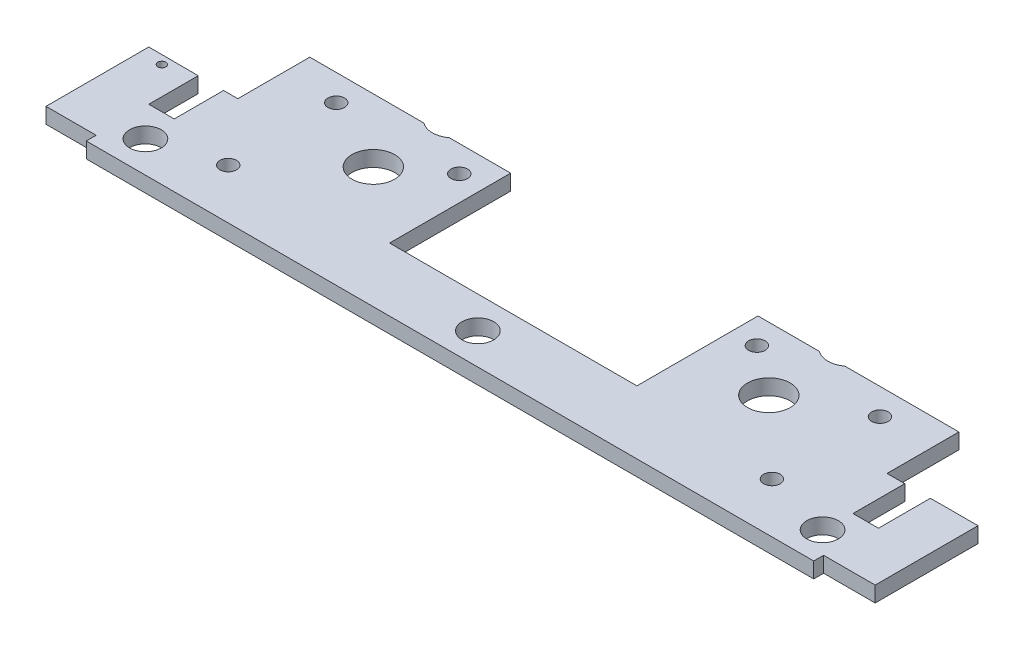
SolidWorks part; units mm, degrees
material "Copper"
ref_plane "Front Plane" through (0, 0, 0) normal (0, 0, 1) x (1, 0, 0)
ref_plane "Top Plane" through (0, 0, 0) normal (0, 1, 0) x (1, 0, 0)
ref_plane "Right Plane" through (0, 0, 0) normal (1, 0, 0) x (0, 0, -1)
sketch "Sketch1" plane through (0, 0, 0) normal (0, 1, 0) x (1, 0, 0)
  line L0 (44.3513, -40.0144) -> (37.1363, -40.0144)
  line L1 (0, 0) -> (0, -46.6159) construction
  line L2 (-19.6486, -28.7674) -> (44.3513, -28.7674) construction
  line L3 (-36.4337, -40.0144) -> (-36.4337, -46.6159)
  line L4 (37.1363, -40.0144) -> (37.1363, -46.6159)
  line L5 (-36.4337, -40.0144) -> (-43.6487, -40.0144)
  line L6 (-32.4727, -10.3704) -> (-32.4727, -29.6479)
  line L7 (-32.4727, 38.1938) -> (-32.4727, -29.6479) construction
  line L8 (-19.6486, -20.6394) -> (46.7444, -20.6394) construction
  line L9 (-42.3787, -29.6159) -> (-32.4727, -29.6479)
  line L10 (-12.1556, -10.3704) -> (-32.4727, -10.3704)
  line L11 (29.9683, -46.6159) -> (37.1363, -46.6159)
  line L12 (44.3513, -40.0144) -> (44.3513, -31.6519)
  line L13 (42.3513, -29.6159) -> (38.7463, -29.6159)
  line L14 (38.7463, -29.6159) -> (33.1753, -29.6479)
  line L15 (-11.5577, -34.6159) -> (-12.1556, -34.6159)
  line L16 (-12.1556, -34.6159) -> (-12.1556, -10.3704)
  line L17 (33.1753, -29.6479) -> (33.1753, 37.3661) construction
  line L18 (33.1753, -12.9294) -> (33.1753, -29.6479)
  line L19 (12.8581, -10.3704) -> (33.1753, -10.3704)
  line L20 (33.1753, -10.3704) -> (33.1753, -12.9294)
  line L21 (-43.6487, -29.6479) -> (-43.6487, -44.6339) construction
  line L22 (-43.6487, -30.8859) -> (-43.6487, -40.0144)
  line L23 (-36.4337, -46.6159) -> (-30.0837, -46.6159)
  line L24 (-30.0837, -46.6159) -> (29.9683, -46.6159)
  line L25 (-11.5577, -34.6159) -> (12.2603, -34.6159)
  line L28 (-43.6487, -30.8859) -> (-43.6487, -29.6479)
  line L29 (-43.6487, -29.6479) -> (-42.3787, -29.6159)
  line L30 (44.3513, -31.6519) -> (44.3513, -29.6159)
  line L31 (44.3513, -29.6159) -> (42.3513, -29.6159)
  line L32 (12.2603, -34.6159) -> (12.8581, -34.6159)
  line L33 (12.8581, -34.6159) -> (12.8581, -10.3704)
  circle A2 centre (-19.6486, -28.7674) radius 2.159
  circle A3 centre (-19.6486, -20.6394) radius 2.159
  circle A4 centre (20.3514, -20.6394) radius 2.159
  circle A5 centre (20.3514, -28.7674) radius 2.159
  dimension "D8" = 4.318
  dimension "D3" = 4.318
  dimension "D6" = 4.318
  dimension "D9" = 4.318
  dimension "D10" = 8.128
  dimension "D1" = 12
  dimension "D4" = 0
  dimension "D11" = 8.128
  dimension "D12" = 0
extrude "Boss-Extrude1" add sketch "Sketch1" along normal blind 1.575
sketch "Sketch2" plane through (0, 0, 0) normal (0, -1, 0) x (1, 0, 0)
  line L2 (-49.1064, 40.0144) -> (44.3513, 40.0144)
  line L4 (-49.1064, 40.0144) -> (-49.1064, 46.6164)
  line L6 (-49.1064, 46.6164) -> (44.3513, 46.6164)
  line L7 (44.3513, 40.0144) -> (44.3513, 46.6164)
  line L10 (-49.1064, 40.0144) -> (44.3513, 46.6164) construction
  line L12 (-49.1064, 46.6164) -> (44.3513, 40.0144) construction
  point P0 (-2.3775, 43.3154)
  dimension "D1" = 6.602
extrude "Cut-Extrude1" cut sketch "Sketch2" against normal through all
sketch "Sketch3" plane through (0, 0, 0) normal (0, -1, 0) x (1, 0, 0)
  line L0 (-41.5047, 40.0144) -> (-41.5047, 29.6188)
  line L1 (-43.6487, 40.0144) -> (44.3513, 40.0144) construction
  line L3 (-32.4727, 29.6479) -> (-42.3787, 29.6159) construction
  line L4 (-41.5047, 29.6188) -> (-34.6297, 29.641)
  line L8 (-41.5047, 40.0144) -> (-48.1288, 40.0144)
  line L9 (-48.1288, 40.0144) -> (-48.1288, 8.9761)
  line L10 (-48.1288, 8.9761) -> (-34.6297, 8.9761)
  line L11 (-34.6297, 29.641) -> (-34.6297, 8.9761)
  dimension "D1" = 6.6241
  dimension "D2" = 6.875
  dimension "D3" = 31.0383
  dimension "D4" = 20.6649
  dimension "D5" = 10.3956
extrude "Cut-Extrude2" cut sketch "Sketch3" against normal through all
sketch "Sketch4" plane through (0, 0, 0) normal (0, -1, 0) x (1, 0, 0)
  line L0 (42.3513, 40.0144) -> (42.3513, 32.4201)
  line L1 (35.4763, 29.6159) -> (35.4763, 10.3704)
  line L2 (35.4763, 10.3704) -> (54.7109, 10.3704)
  line L7 (54.7109, 10.3704) -> (54.7109, 40.0144)
  line L8 (-41.5047, 40.0144) -> (44.3513, 40.0144) construction
  line L11 (44.3513, 40.0144) -> (44.3513, 29.6159) construction
  line L12 (42.3513, 32.4201) -> (42.3513, 29.6159)
  line L13 (44.3513, 29.6159) -> (38.7463, 29.6159) construction
  line L14 (42.3513, 29.6159) -> (35.4763, 29.6159)
  line L15 (42.3513, 40.0144) -> (54.7109, 40.0144)
  dimension "D2" = 2
extrude "Cut-Extrude3" cut sketch "Sketch4" against normal through all
sketch "Sketch6" plane through (0, 0, 0) normal (0, -1, 0) x (-1, 0, 0)
  circle A0 centre (27.1416, -35.9479) radius 0.8382
  circle A1 centre (27.1416, -25.0259) radius 0.8382
  circle A2 centre (14.6956, -25.0259) radius 0.8382
  circle A3 centre (-15.3981, -25.0259) radius 0.8382
  circle A4 centre (-27.8444, -25.0259) radius 0.8382
  circle A5 centre (-27.8444, -35.9479) radius 0.8382
extrude "Cut-Extrude4" cut sketch "Sketch6" against normal blind 2.54
sketch "Sketch7" plane through (0, 0, 0) normal (0, -1, 0) x (1, 0, 0)
  line L0 (-32.4727, 10.3704) -> (-32.4727, 29.6479) construction
  line L1 (-32.4727, 22.3704) -> (33.1753, 22.3704)
  line L2 (-32.4727, 22.3704) -> (-32.4727, 10.3704)
  line L3 (-32.4727, 10.3704) -> (33.1753, 10.3704)
  line L4 (33.1753, 22.3704) -> (33.1753, 10.3704)
  dimension "D1" = 12
extrude "Cut-Extrude5" cut sketch "Sketch7" against normal through all
sketch "Sketch11" plane through (0, 1.575, 0) normal (0, 1, 0) x (1, 0, 0)
  circle A0 centre (-39.3048, -30.495) radius 0.4126
extrude "ID HOLE" cut sketch "Sketch11" against normal through all
sketch "Sketch12" plane through (0, 0, 0) normal (0, -1, 0) x (-1, 0, 0)
  line L0 (42.3787, -29.6159) -> (32.4727, -29.6479) construction
  line L1 (36.4887, -29.635) -> (33.9137, -29.635)
  line L2 (36.4887, -29.635) -> (36.4887, -34.635)
  line L3 (36.4887, -34.635) -> (33.9137, -34.635)
  line L4 (33.9137, -29.635) -> (33.9137, -34.635)
  dimension "D1" = 2.575
  dimension "D2" = 5
  dimension "D3" = 5.016
extrude "Notch for BPR (TOP VIEW)" cut sketch "Sketch12" against normal through all
sketch "Sketch14" plane through (0, 0, 0) normal (0, -1, 0) x (-1, 0, 0)
  line L1 (-42.3513, -40.0144) -> (-42.3513, -27.0505) construction
  line L2 (-33.1753, -22.3704) -> (-21.6417, -22.3704) construction
  line L4 (-34.9663, -34.873) -> (-37.5413, -34.873)
  line L5 (-34.9663, -34.873) -> (-34.9663, -22.3704)
  line L6 (-34.9663, -22.3704) -> (-37.5413, -22.3704)
  line L7 (-37.5413, -34.873) -> (-37.5413, -22.3704)
  dimension "D1" = 79.046
  dimension "D2" = 2.575
extrude "Notch for BPL (TOP VIEW)" cut sketch "Sketch14" against normal through all contours L5 L6 L7 L4
sketch "Sketch17" plane through (0, 0, 0) normal (0, -1, 0) x (1, 0, 0)
  line L0 (37.1363, 40.0144) -> (37.1363, 46.6159) construction
  line L1 (-36.4337, 40.0144) -> (37.1363, 40.0144)
  line L2 (-36.4337, 40.0144) -> (-36.4337, 41.0144)
  line L3 (-36.4337, 41.0144) -> (37.1363, 41.0144)
  line L4 (37.1363, 40.0144) -> (37.1363, 41.0144)
  dimension "D1" = 1
extrude "Create Lip for M3 Spacer Hole" add sketch "Sketch17" against normal blind 1.575
sketch "Sketch15" plane through (0, 0, 0) normal (0, -1, 0) x (1, 0, 0)
  line L0 (-2.4821, 41.0144) -> (2.1436, 41.0144) construction
  line L2 (37.1363, 41.0144) -> (-36.4337, 41.0144) construction
  line L3 (-2.17, 34.6159) -> (2.1436, 34.6159) construction
  line L6 (-11.5577, 34.6159) -> (12.2603, 34.6159) construction
  line L7 (0, 41.0144) -> (-0.0132, 34.6159) construction
  line L8 (0, 0) -> (0, 46.6159) construction
  line L9 (-0.0066, 37.8358) -> (2.1436, 37.8358) construction
  line L10 (-0.0066, 37.8358) -> (-1.1093, 37.8358) construction
  line L11 (-1000.0066, 37.8358) -> (48999.9934, 37.8358)
  circle A0 centre (-0.0066, 37.8358) radius 1.6
  circle A1 centre (-33.6287, 37.8358) radius 1.6
  circle A2 centre (34.8513, 37.8358) radius 1.6
  dimension "D1" = 3.2
  dimension "D2" = 3.2
  dimension "D4" = 3.2
  dimension "D3" = 2.805
  dimension "D5" = 7.5
extrude "HOLE for M3 Spacer" cut sketch "Sketch15" against normal through all
